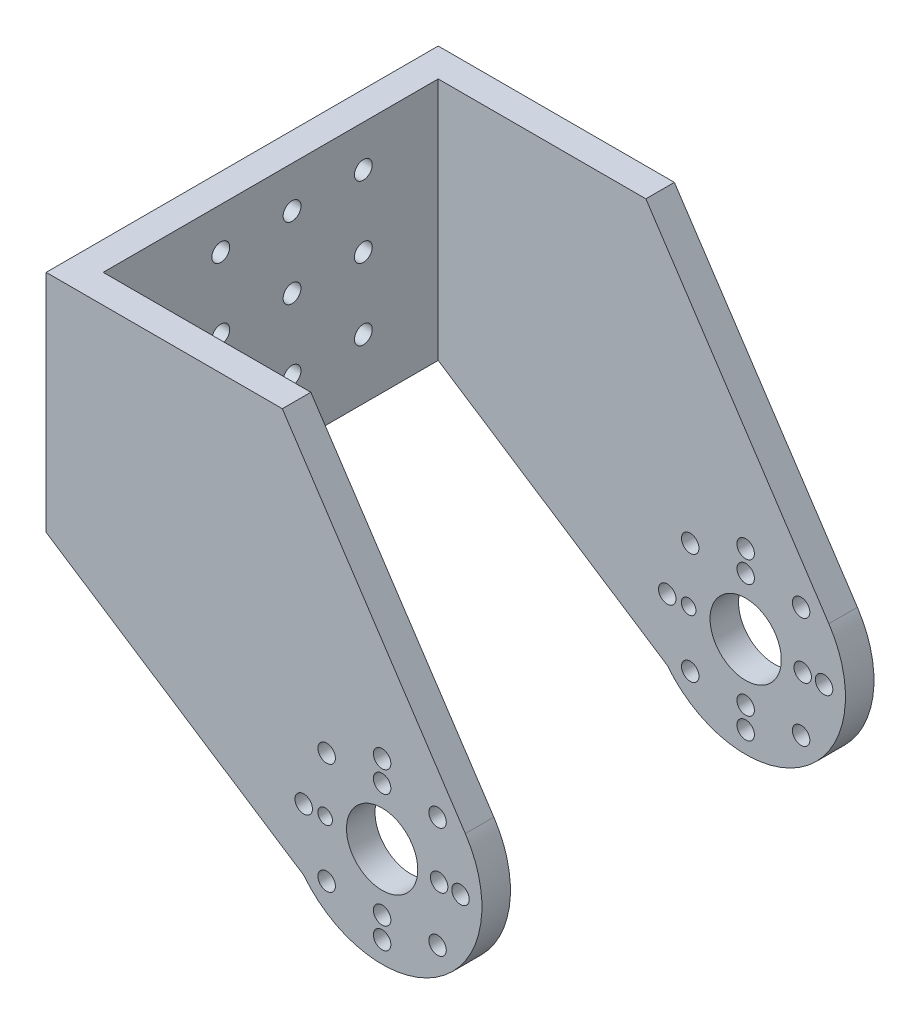
SolidWorks part; units mm, degrees
ref_plane "정면" through (0, 0, 0) normal (0, 0, 1) x (1, 0, 0)
ref_plane "윗면" through (0, 0, 0) normal (0, 1, 0) x (1, 0, 0)
ref_plane "우측면" through (0, 0, 0) normal (1, 0, 0) x (0, 0, -1)
sketch "스케치1" plane through (0, 0, 0) normal (0, 0, 1) x (1, 0, 0)
  line L0 (11.674, 7.7277) -> (-14, 46.5127)
  line L4 (-14, 46.5127) -> (-47.1329, 46.5127)
  line L5 (-11, -8.6603) -> (-47.1329, 14.9217)
  line L8 (-47.1329, 46.5127) -> (-47.1329, 14.9217)
  circle A18 centre (0, 0) radius 5
  circle A19 centre (0, 8) radius 1.225
  circle A20 centre (0, 11) radius 1.225
  arc A21 (-11, -8.6603) -> (11.674, 7.7277) centre (0, 0) ccw
  circle A22 centre (7.7782, 7.7782) radius 1.225
  circle A23 centre (8, 0) radius 1.225
  circle A24 centre (11, 0) radius 1.225
  circle A25 centre (7.7782, -7.7782) radius 1.225
  circle A26 centre (0, -8) radius 1.225
  circle A27 centre (0, -11) radius 1.225
  circle A28 centre (-7.7782, -7.7782) radius 1.225
  circle A29 centre (-8, 0) radius 1.025
  circle A30 centre (-11, 0) radius 1.225
  circle A31 centre (-7.7782, 7.7782) radius 1.225
  dimension "D1" = 10
  dimension "D3" = 2.45
  dimension "D5" = 28
  dimension "D6" = 2.05
  dimension "D2" = 8
  dimension "D4" = 11
  dimension "D7" = 7.7782
  dimension "D8" = 8
  dimension "D9" = 11
  dimension "D10" = 11.674
  dimension "D11" = 7.7782
  dimension "D12" = 8
  dimension "D13" = 14
  dimension "D14" = 47.1329
  dimension "D15" = 7.7782
  dimension "D16" = 11
  dimension "D17" = 14.9217
  dimension "D18" = 7.7782
  dimension "D19" = 8
  dimension "D20" = 11
extrude "보스-돌출1" add sketch "스케치1" along normal blind 55
sketch "스케치2" plane through (0, 46.5127, 0) normal (0, 1, 0) x (1, 0, 0)
  line L0 (-43.1329, -4) -> (14, -4)
  line L1 (14, -55) -> (14, 0) construction
  line L2 (14, -4) -> (14, -51)
  line L3 (14, -51) -> (-43.1329, -51)
  line L4 (-43.1329, -51) -> (-43.1329, -4)
  line L5 (-14, 0) -> (-47.1329, 0) construction
  line L6 (-47.1329, -55) -> (-47.1329, 0) construction
  point P4 (-30.5665, 0)
  dimension "D1" = 4
  dimension "D2" = 47
  dimension "D3" = 4
extrude "컷-돌출1" cut sketch "스케치2" against normal blind 66
sketch "스케치3" plane through (-47.1329, 0, 0) normal (-1, 0, 0) x (0, 0, 1)
  line L0 (0, 46.5127) -> (0, 14.9217) construction
  line L3 (55, 14.9217) -> (0, 14.9217) construction
  circle A0 centre (24.5, 30.7172) radius 1.25
  circle A1 centre (14.5, 40.7172) radius 1.25
  circle A2 centre (34.5, 30.7172) radius 1.25
  circle A3 centre (24.5, 40.7172) radius 1.25
  circle A4 centre (14.5, 30.7172) radius 1.25
  circle A5 centre (34.5, 40.7172) radius 1.25
  circle A6 centre (14.5, 20.7172) radius 1.25
  circle A7 centre (24.5, 20.7172) radius 1.25
  circle A8 centre (34.5, 20.7172) radius 1.25
  circle A45 centre (29.5, 30.7172) radius 1.25 [skipped]
  circle A46 centre (19.5, 30.7172) radius 1.25 [skipped]
  dimension "D1" = 2
  dimension "D5" = 2.5
  dimension "D6" = 14.5
  dimension "D7" = 19.5
  dimension "D8" = 29.5
  dimension "D9" = 5.7955
  dimension "D10" = 15.7955
  dimension "D11" = 25.7955
  dimension "D2" = 3
  dimension "D3" = 3
  dimension "D4" = 2
extrude "컷-돌출2" cut sketch "스케치3" against normal blind 49
